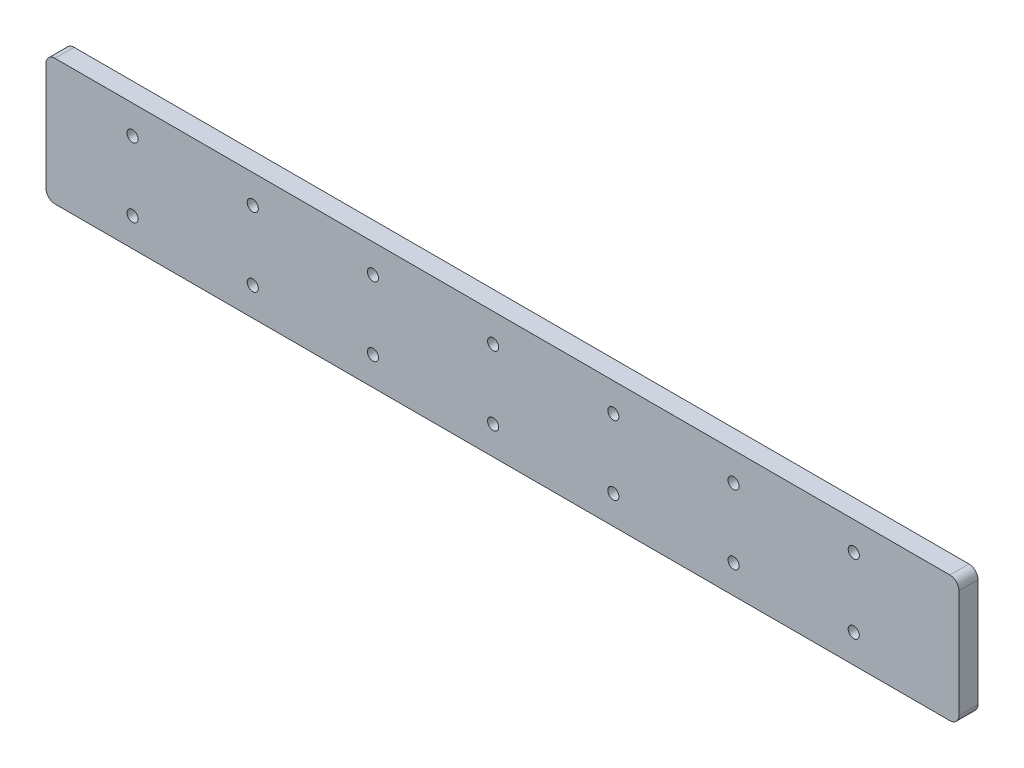
SolidWorks part; units mm, degrees
material "Balsa"
ref_plane "Front Plane" through (0, 0, 0) normal (0, 0, 1) x (1, 0, 0)
ref_plane "Top Plane" through (0, 0, 0) normal (0, 1, 0) x (1, 0, 0)
ref_plane "Right Plane" through (0, 0, 0) normal (1, 0, 0) x (0, 0, -1)
sketch "Sketch1" plane through (0, 0, 0) normal (0, 0, 1) x (1, 0, 0)
  line L0 (0, 0) -> (-10, 0) construction
  line L1 (0, 21) -> (-303.8, 21)
  line L2 (0, 21) -> (0, -21)
  line L3 (0, -21) -> (-303.8, -21)
  line L4 (-303.8, 21) -> (-303.8, -21)
  line L5 (0, 0) -> (20, 0) construction
  circle A0 centre (5, 11.5) radius 1.85 construction
  circle A1 centre (-35, 11.5) radius 1.85
  circle A2 centre (-75, 11.5) radius 1.85
  circle A3 centre (-115, 11.5) radius 1.85
  circle A4 centre (-155, 11.5) radius 1.85
  circle A5 centre (-195, 11.5) radius 1.85
  circle A6 centre (-235, 11.5) radius 1.85
  circle A7 centre (-275, 11.5) radius 1.85
  circle A8 centre (-315, 11.5) radius 1.85 construction
  circle A9 centre (-275, -11.5) radius 1.85
  circle A10 centre (-235, -11.5) radius 1.85
  circle A11 centre (-195, -11.5) radius 1.85
  circle A12 centre (-155, -11.5) radius 1.85
  circle A13 centre (-115, -11.5) radius 1.85
  circle A14 centre (-75, -11.5) radius 1.85
  circle A15 centre (-35, -11.5) radius 1.85
  dimension "D4" = 20
  dimension "D6" = 3.7
  dimension "D8" = 40
  dimension "D1" = 42
  dimension "D2" = 10
  dimension "D3" = 11.5
  dimension "D5" = 15
  dimension "D9" = 303.8
  dimension "D7" = 9
extrude "Boss-Extrude1" add sketch "Sketch1" along normal blind 6.35
fillet "Fillet1" radius 3 4 edges at (-303.8, -21, 3.175) (0, -21, 3.175) (0, 21, 3.175) (-303.8, 21, 3.175)
